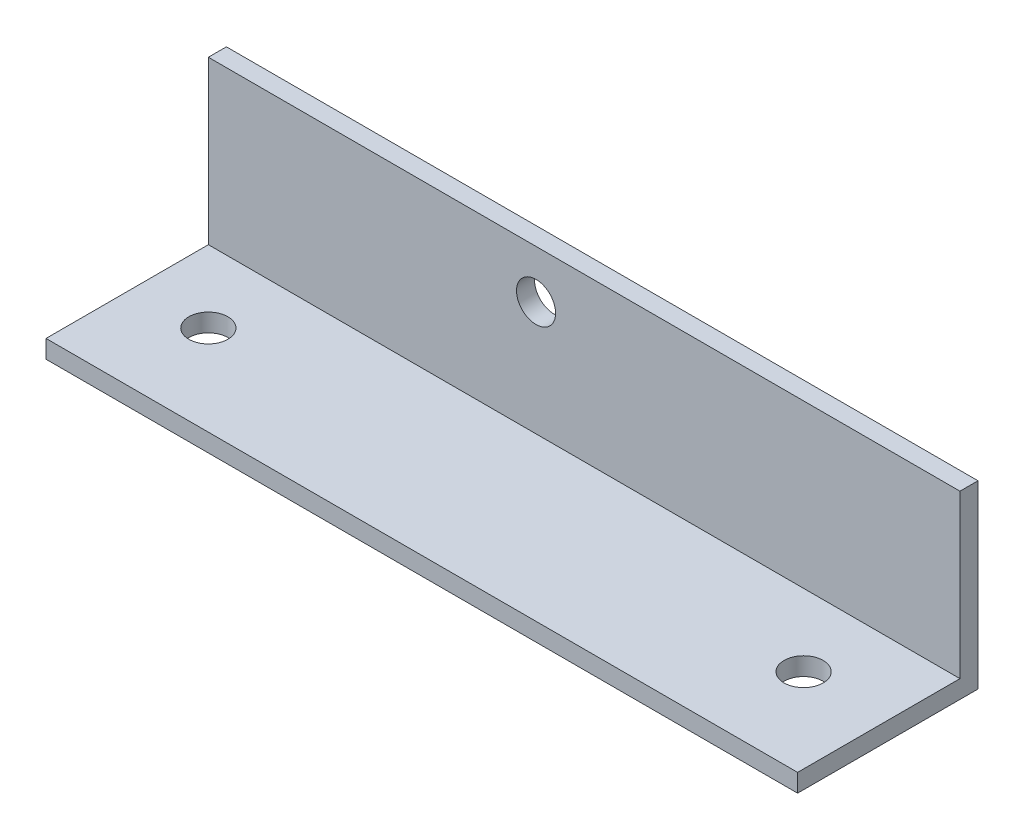
SolidWorks part; units mm, degrees
material "6061 Alloy"
ref_plane "Front Plane" through (0, 0, 0) normal (0, 0, 1) x (1, 0, 0)
ref_plane "Top Plane" through (0, 0, 0) normal (0, 1, 0) x (1, 0, 0)
ref_plane "Right Plane" through (0, 0, 0) normal (1, 0, 0) x (0, 0, -1)
sketch "Sketch1" plane through (0, 0, 0) normal (0, 0, 1) x (1, 0, 0)
  line L1 (-62.5, -15) -> (62.5, -15)
  line L2 (-62.5, -15) -> (-62.5, 15)
  line L3 (-62.5, 15) -> (62.5, 15)
  line L4 (62.5, -15) -> (62.5, 15)
  line L5 (-62.5, -15) -> (62.5, 15) construction
  line L6 (-62.5, 15) -> (62.5, -15) construction
  point P0 (0, 0)
  dimension "D1" = 125
  dimension "D2" = 30
extrude "Boss-Extrude1" add sketch "Sketch1" along normal blind 3
sketch "Sketch2" plane through (0, 0, 3) normal (0, 0, 1) x (1, 0, 0)
  line L0 (-62.5, -15) -> (62.5, -15) construction
  line L1 (-62.5, -15) -> (62.5, -15)
  line L2 (-62.5, -15) -> (-62.5, -12)
  line L3 (-62.5, 15) -> (-62.5, -15) construction
  line L4 (-62.5, -12) -> (62.5, -12)
  line L5 (62.5, -15) -> (62.5, 15) construction
  line L6 (62.5, -12) -> (62.5, -15)
  dimension "D1" = 3
extrude "Boss-Extrude2" add sketch "Sketch2" along normal blind 27
hole_wizard "Ø6.5 (6.5) Diameter Hole1" positions "Sketch4" profile "Sketch5" hole size "Ø6.5" standard "ANSI Metric"
sketch "Sketch4" plane through (0, -12, 0) normal (0, 1, 0) x (1, 0, 0)
  line L0 (62.5, -30) -> (62.5, -3) construction
  line L1 (62.5, -3) -> (-62.5, -3) construction
  line L2 (-62.5, -30) -> (-62.5, -3) construction
  point P0 (48.5, -15)
  point P3 (-50.5, -15)
  dimension "D1" = 14
  dimension "D2" = 12
  dimension "D3" = 12
  dimension "D4" = 12
sketch "Sketch5" plane through (48.5, -12, 15) normal (1, 0, 0) x (0, 0, 1)
  line L0 (0, 0) -> (0, 11.9528)
  line L1 (0, 11.9528) -> (3.25, 10)
  line L2 (3.25, 10) -> (3.25, 0)
  line L5 (3.25, 0) -> (0, 0)
  line L10 (0, 11.9528) -> (-3.25, 10) construction
  line L11 (0, -6.35) -> (0, 107.95) construction
  dimension "Hole Dia." = 6.5
  dimension "Hole Depth" = 10
  dimension "Drill Angle" = 118
hole_wizard "Ø6.5 (6.5) Diameter Hole2" positions "Sketch6" profile "Sketch7" hole size "Ø6.5" standard "ANSI Metric"
sketch "Sketch6" plane through (0, 0, 0) normal (0, 0, -1) x (-1, 0, 0)
  point P0 (8, 7)
sketch "Sketch7" plane through (-8, 7, 0) normal (1, 0, 0) x (0, 1, 0)
  line L0 (0, 0) -> (0, 33.9528)
  line L1 (0, 33.9528) -> (3.25, 32)
  line L2 (3.25, 32) -> (3.25, 0)
  line L5 (3.25, 0) -> (0, 0)
  line L10 (0, 33.9528) -> (-3.25, 32) construction
  line L11 (0, -6.35) -> (0, 107.95) construction
  dimension "Hole Dia." = 6.5
  dimension "Hole Depth" = 32
  dimension "Drill Angle" = 118
